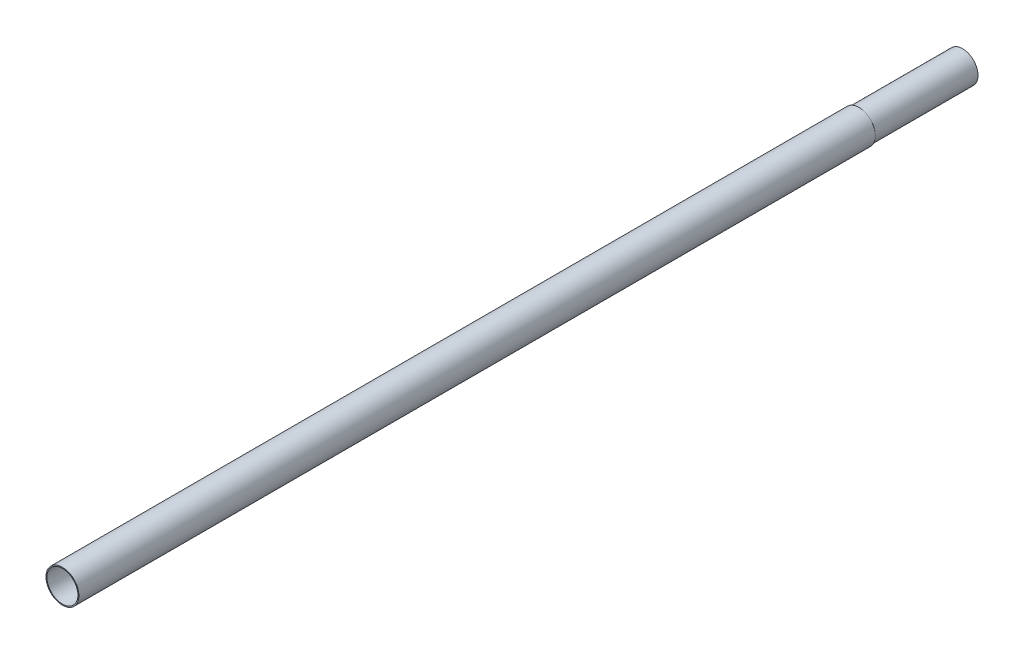
SolidWorks part; units mm, degrees
ref_plane "Front Plane" through (0, 0, 0) normal (0, 0, 1) x (1, 0, 0)
ref_plane "Top Plane" through (0, 0, 0) normal (0, 1, 0) x (1, 0, 0)
ref_plane "Right Plane" through (0, 0, 0) normal (1, 0, 0) x (0, 0, -1)
sketch "Sketch1" plane through (0, 0, 0) normal (0, 0, 1) x (1, 0, 0)
  circle A0 centre (0, 0) radius 25.4
  circle A1 centre (0, 0) radius 23.9
  dimension "D1" = 50.8
  dimension "D2" = 47.8
extrude "Boss-Extrude1" add sketch "Sketch1" along normal blind 1230
ref_plane "Plane1" through (0, 0, -160) normal (0, 0, -1) x (-1, 0, 0)
sketch "Sketch2" plane through (0, 0, -160) normal (0, 0, -1) x (-1, 0, 0)
  circle A0 centre (0, 0) radius 23.9
  circle A1 centre (0, 0) radius 22.4
  dimension "D1" = 47.8
  dimension "D2" = 44.8
extrude "Boss-Extrude2" add sketch "Sketch2" against normal up to surface (160 mm away) separate body up to face at (25.4, 0, 0)
